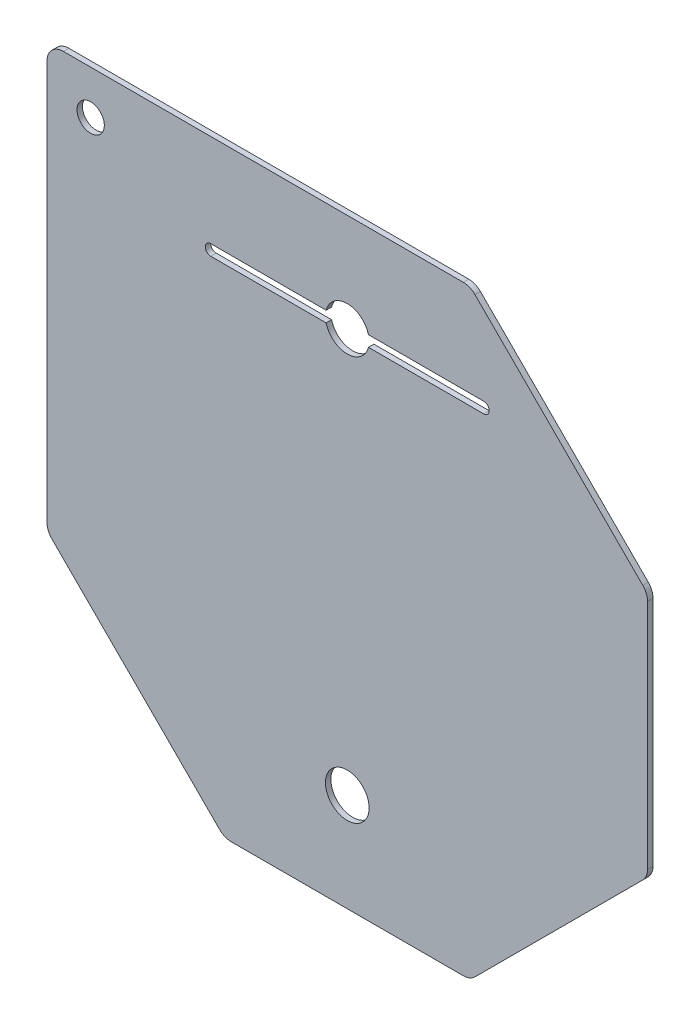
SolidWorks part; units mm, degrees
ref_plane "Front Plane" through (0, 0, 0) normal (0, 0, 1) x (1, 0, 0)
ref_plane "Top Plane" through (0, 0, 0) normal (0, 1, 0) x (1, 0, 0)
ref_plane "Right Plane" through (0, 0, 0) normal (1, 0, 0) x (0, 0, -1)
sketch "Sketch1" plane through (0, 0, 0) normal (0, 0, 1) x (1, 0, 0)
  line L0 (55, -21.2574) -> (55, 21.2574)
  line L1 (-55, 55) -> (55, 55) construction
  line L2 (-55, 55) -> (-55, -55) construction
  line L3 (-55, -55) -> (55, -55) construction
  line L4 (55, 55) -> (55, -55) construction
  line L5 (0, -73.3123) -> (0, 99.7862) construction
  line L6 (-89.0876, 0) -> (90.8924, 0) construction
  line L7 (-52, 55) -> (21.2574, 55)
  line L8 (-21.2574, -55) -> (21.2574, -55)
  line L9 (-55, -21.2574) -> (-55, 52)
  line L10 (-25, 37) -> (25, 37) construction
  line L11 (-54.1213, -23.3787) -> (-23.3787, -54.1213)
  line L12 (23.3787, -54.1213) -> (54.1213, -23.3787)
  line L13 (54.1213, 23.3787) -> (23.3787, 54.1213)
  line L14 (-25, 38) -> (-3.873, 38)
  line L15 (-25, 36) -> (-3.873, 36)
  line L16 (3.873, 38) -> (25, 38)
  line L17 (3.873, 36) -> (25, 36)
  circle A0 centre (-47, 47) radius 2.5
  arc A1 (-55, 52) -> (-52, 55) centre (-52, 52) cw
  arc A2 (-3.873, 36) -> (3.873, 36) centre (0, 37) ccw
  arc A3 (-25, 38) -> (-25, 36) centre (-25, 37) ccw
  arc A4 (25, 36) -> (25, 38) centre (25, 37) ccw
  arc A5 (54.1213, -23.3787) -> (55, -21.2574) centre (52, -21.2574) ccw
  arc A6 (23.3787, -54.1213) -> (21.2574, -55) centre (21.2574, -52) cw
  arc A7 (-21.2574, -55) -> (-23.3787, -54.1213) centre (-21.2574, -52) cw
  arc A8 (-54.1213, -23.3787) -> (-55, -21.2574) centre (-52, -21.2574) cw
  arc A9 (54.1213, 23.3787) -> (55, 21.2574) centre (52, 21.2574) cw
  arc A10 (21.2574, 55) -> (23.3787, 54.1213) centre (21.2574, 52) cw
  circle A11 centre (0, -37) radius 4
  arc A12 (3.873, 38) -> (-3.873, 38) centre (0, 37) ccw
  point P24 (0, 37)
  point P31 (55, -22.5)
  point P34 (22.5, -55)
  point P37 (-22.5, -55)
  point P40 (-55, -22.5)
  point P43 (55, 22.5)
  point P46 (22.5, 55)
  dimension "D10" = 5
  dimension "D13" = 3
  dimension "D14" = 8
  dimension "D18" = 3
  dimension "D19" = 8
  dimension "D22" = 1
  dimension "D23" = 1
  dimension "D1" = 110
  dimension "D2" = 55
  dimension "D3" = 110
  dimension "D4" = 55
  dimension "D5" = 45
  dimension "D6" = 22.5
  dimension "D7" = 45
  dimension "D8" = 22.5
  dimension "D9" = 32.5
  dimension "D11" = 8
  dimension "D12" = 8
  dimension "D15" = 25
  dimension "D16" = 2
  dimension "D17" = 37
  dimension "D20" = 37
  dimension "D21" = 50
extrude "Boss-Extrude1" add sketch "Sketch1" along normal blind 1
